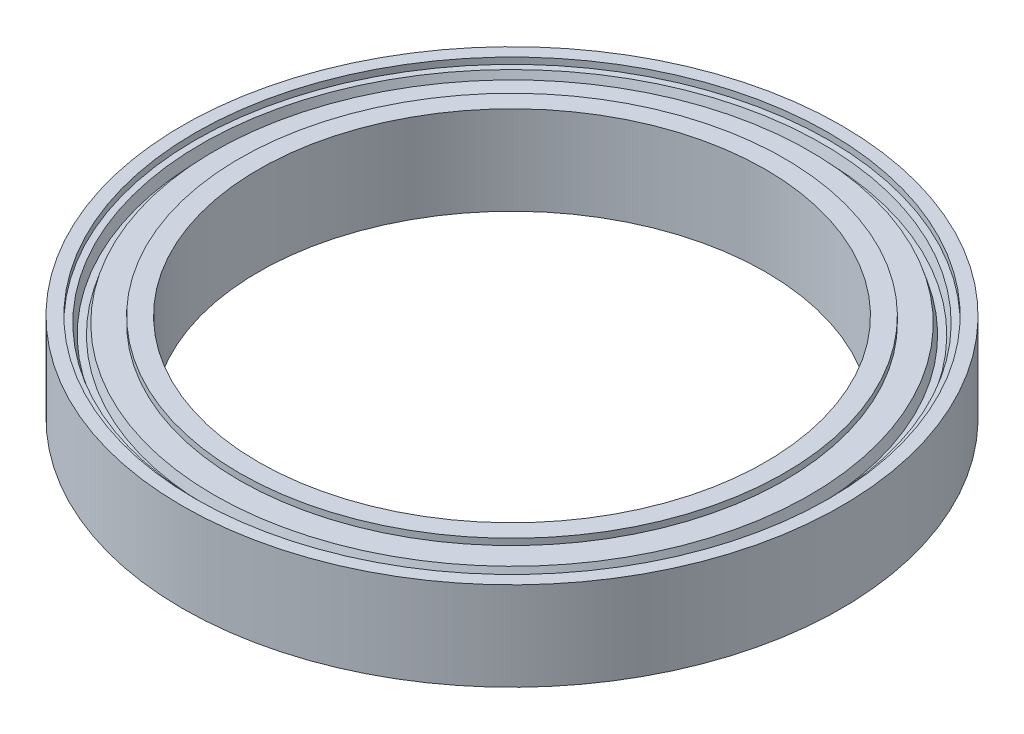
SolidWorks part; units mm, degrees
material "06ХН28МДТ ГОСТ 4543-71"
ref_plane "Спереди" through (0, 0, 0) normal (0, 0, 1) x (1, 0, 0)
ref_plane "Сверху" through (0, 0, 0) normal (0, 1, 0) x (1, 0, 0)
ref_plane "Справа" through (0, 0, 0) normal (1, 0, 0) x (0, 0, -1)
other "Configuration Table"
sketch "Эскиз1" plane through (0, 0, 0) normal (0, 1, 0) x (1, 0, 0)
  circle A0 centre (0, 0) radius 20
  circle A1 centre (0, 0) radius 26
  dimension "D1" = 52
  dimension "D2" = 40
extrude "Бобышка-Вытянуть1" add sketch "Эскиз1" along normal blind 7
sketch "Эскиз2" plane through (0, 7, 0) normal (0, 1, 0) x (1, 0, 0)
  circle A0 centre (0, 0) radius 21.5
  circle A1 centre (0, 0) radius 25
  dimension "D1" = 50
  dimension "D2" = 43
extrude "Вырез-Вытянуть1" cut sketch "Эскиз2" against normal blind 0.5
sketch "Эскиз3" plane through (0, 6.5, 0) normal (0, 1, 0) x (1, 0, 0)
  circle A0 centre (0, 0) radius 24.5
  circle A1 centre (0, 0) radius 23.5
  dimension "D1" = 47
  dimension "D2" = 49
extrude "Вырез-Вытянуть2" cut sketch "Эскиз3" against normal blind 0.8 draft 17
sketch "Эскиз4" plane through (0, 0, 0) normal (0, -1, 0) x (1, 0, 0)
  circle A0 centre (0, 0) radius 24.5
  circle A1 centre (0, 0) radius 21.5
  dimension "D1" = 43
  dimension "D2" = 49
extrude "Вырез-Вытянуть3" cut sketch "Эскиз4" against normal blind 0.5
